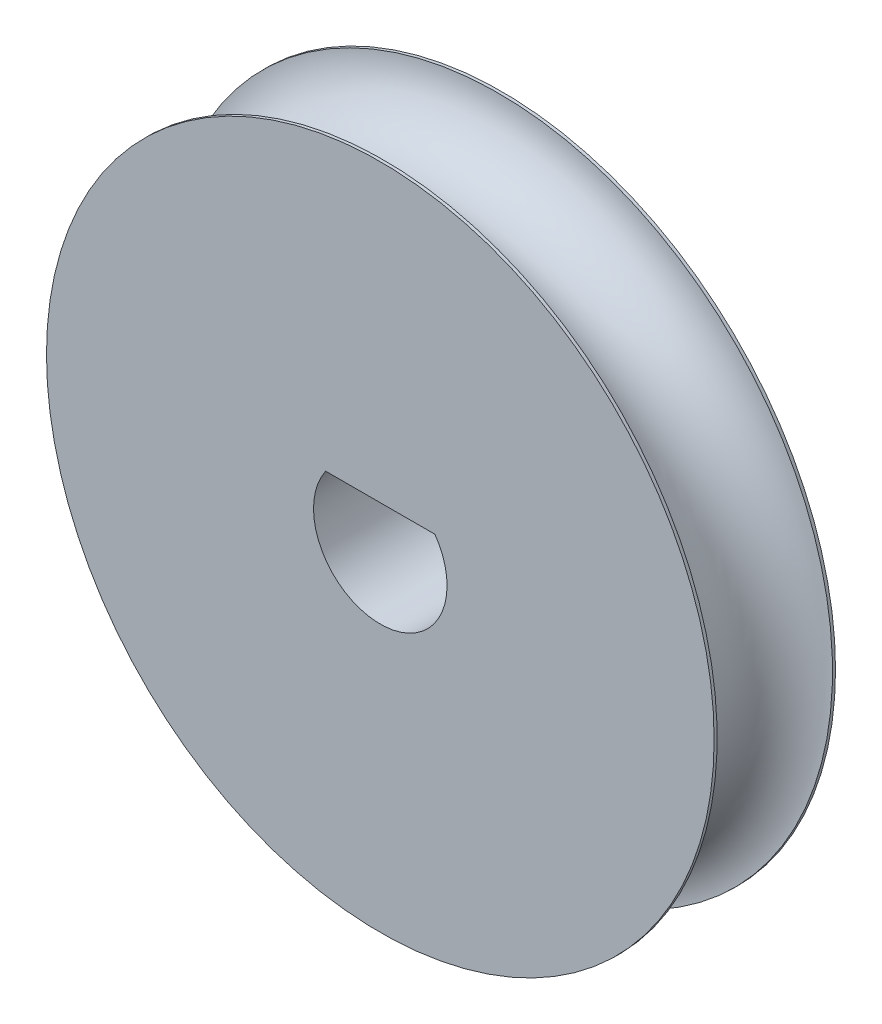
SolidWorks part; units mm, degrees
ref_plane "Front Plane" through (0, 0, 0) normal (0, 0, 1) x (1, 0, 0)
ref_plane "Top Plane" through (0, 0, 0) normal (0, 1, 0) x (1, 0, 0)
ref_plane "Right Plane" through (0, 0, 0) normal (1, 0, 0) x (0, 0, -1)
sketch "Sketch1" plane through (0, 0, 0) normal (0, 0, 1) x (1, 0, 0)
  circle A0 centre (0, 0) radius 5.5
  circle A1 centre (0, 0) radius 1.1
  dimension "D1" = 11
  dimension "D2" = 2.2
extrude "Boss-Extrude1" add sketch "Sketch1" along normal blind 2
sketch "Sketch2" plane through (0, 0, 2) normal (0, 0, 1) x (1, 0, 0)
  line L0 (-0.9, 0.6325) -> (0.9, 0.6325)
  circle A0 centre (0, 0) radius 1.1 construction
  arc A1 (-0.9, 0.6325) -> (0.9, 0.6325) centre (0, 0) cw
  dimension "D1" = 1.8
extrude "Boss-Extrude3" add sketch "Sketch2" against normal up to surface (2 mm away) contours L0 A1 up to face at (5.5, 0, 0)
sketch "Sketch3" plane through (0, 0, 0) normal (1, 0, 0) x (0, 0, -1)
  line L0 (0, 5.5) -> (-2, 5.5) construction
  line L1 (-1, 5.5) -> (-1, 4.5) construction
  line L2 (-0.05, 5.5) -> (-1.95, 5.5)
  arc A0 (-0.05, 5.5) -> (-1.95, 5.5) centre (-1, 5.5) cw
  dimension "D1" = 0.95
  dimension "D2" = 0.95
  dimension "D3" = 0.95
  dimension "D4" = 1
ref_axis "Axis1" through (0, 0, -0.1) along (0, 0, 1)
revolve "Cut-Revolve1" cut sketch "Sketch3" angle 360 about axis through (0, 0, -0.1) along (0, 0, 1)
